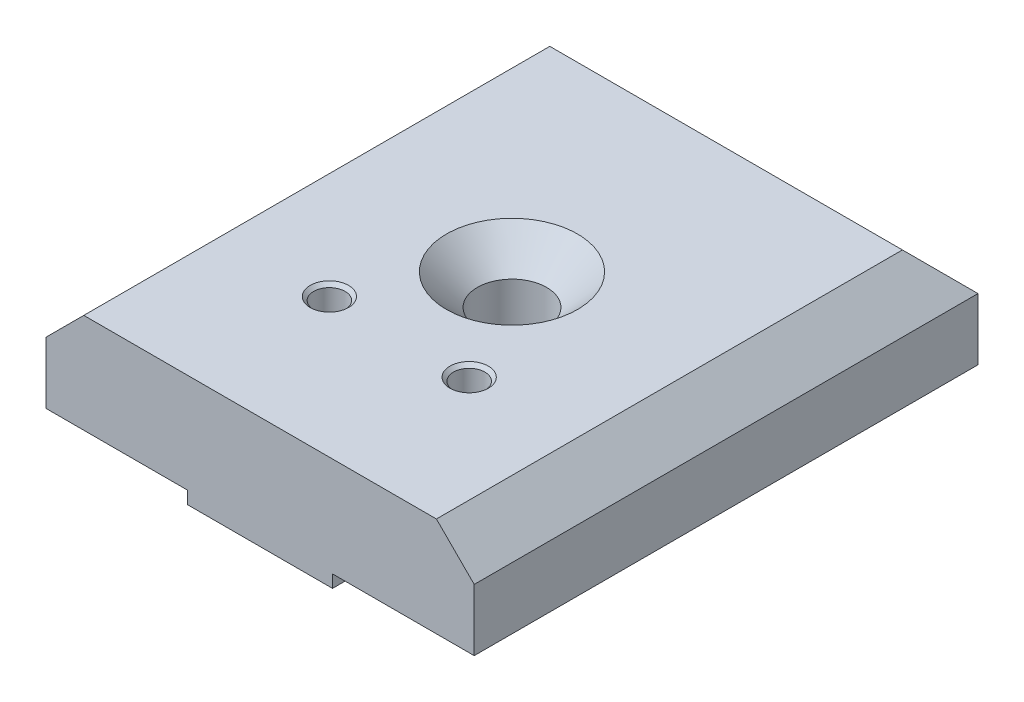
SolidWorks part; units mm, degrees
material "3.1355 (EN-AW 2024)"
ref_plane "Front" through (0, 0, 0) normal (0, 0, 1) x (1, 0, 0)
ref_plane "Top" through (0, 0, 0) normal (0, 1, 0) x (1, 0, 0)
ref_plane "Right" through (0, 0, 0) normal (1, 0, 0) x (0, 0, -1)
sketch "Эскиз1" plane through (0, 0, 0) normal (0, 1, 0) x (1, 0, 0)
  line L1 (-17, 20) -> (17, 20)
  line L2 (-17, 20) -> (-17, -20)
  line L3 (-17, -20) -> (17, -20)
  line L4 (17, 20) -> (17, -20)
  line L5 (-17, 20) -> (17, -20) construction
  line L6 (-17, -20) -> (17, 20) construction
  point P0 (0, 0)
  dimension "D1" = 40
  dimension "D2" = 34
extrude "База" add sketch "Эскиз1" along normal blind 7.9
hole_wizard "Крепление к профилю 40 - M5" positions "Эскиз2" profile "Эскиз3" countersink size "M5" standard "DIN" end condition through all
sketch "Эскиз2" plane through (0, 7.9, 0) normal (0, 1, 0) x (-1, 0, 0)
  point P0 (0, 0)
sketch "Эскиз3" plane through (0, 7.9, 0) normal (1, 0, 0) x (0, 0, 1)
  line L0 (0, 0) -> (0, 7.9)
  line L1 (0, 7.9) -> (2.75, 7.9)
  line L2 (2.75, 7.9) -> (2.75, 2.45)
  line L3 (2.75, 2.45) -> (5.2, 0)
  line L5 (5.2, 0) -> (0, 0)
  line L6 (-2.75, 2.45) -> (-5.2, 0) construction
  line L11 (0, -6.35) -> (0, 107.95) construction
  dimension "Диаметр сквозного отверстия" = 5.5
  dimension "Глубина сквозного отверстия" = 7.9
  dimension "Диаметр передней зенковки" = 10.4
  dimension "Угол передней зенковки" = 90
hole_wizard "Крепление датчика M3" positions "Эскиз6" profile "Эскиз5" tap size "M3" standard "DIN" end condition through all
sketch "Эскиз6" plane through (0, 7.9, 0) normal (0, 1, 0) x (-1, 0, 0)
  line L0 (5.55, 8.95) -> (0, 8.95) construction
  line L1 (0, 8.95) -> (-5.55, 8.95) construction
  point P0 (5.55, 8.95)
  point P3 (-5.55, 8.95)
  dimension "D1" = 11.1
  dimension "D2" = 8.95
sketch "Эскиз5" plane through (-5.55, 7.9, 8.95) normal (1, 0, 0) x (0, 0, 1)
  line L0 (0, 0) -> (0, 7.9)
  line L1 (0, 7.9) -> (1.25, 7.9)
  line L2 (1.25, 7.9) -> (1.25, 0.275)
  line L3 (1.25, 0.275) -> (1.525, 0)
  line L5 (1.525, 0) -> (0, 0)
  line L6 (-1.25, 0.275) -> (-1.525, 0) construction
  line L11 (0, -6.35) -> (0, 107.95) construction
  dimension "Диаметр проходного сверла" = 2.5
  dimension "Глубина проходного сверла" = 7.9
  dimension "Диаметр передней зенковки" = 3.05
  dimension "Угол передней зенковки" = 90
cosmetic thread "Отверстие резьбы1" parameters "D2"=3
cosmetic thread "Отверстие резьбы2" parameters "D2"=3
chamfer "Фаска1" distance 3 angle 45 4 edges at (0, 7.9, 20) (17, 7.9, 0) (0, 7.9, -20) (-17, 7.9, 0)
sketch "Эскиз7" plane through (0, 0, 0) normal (0, -1, 0) x (1, 0, 0)
  line L0 (17, -20) -> (-17, -20) construction
  line L1 (-5.75, 20) -> (5.75, 20)
  line L2 (-5.75, 20) -> (-5.75, -20)
  line L3 (-5.75, -20) -> (5.75, -20)
  line L4 (5.75, 20) -> (5.75, -20)
  line L5 (-5.75, 20) -> (5.75, -20) construction
  line L6 (-5.75, -20) -> (5.75, 20) construction
  point P0 (0, 0)
  dimension "D1" = 11.5
extrude "Направляющая профиля 40" add sketch "Эскиз7" along normal blind 1
